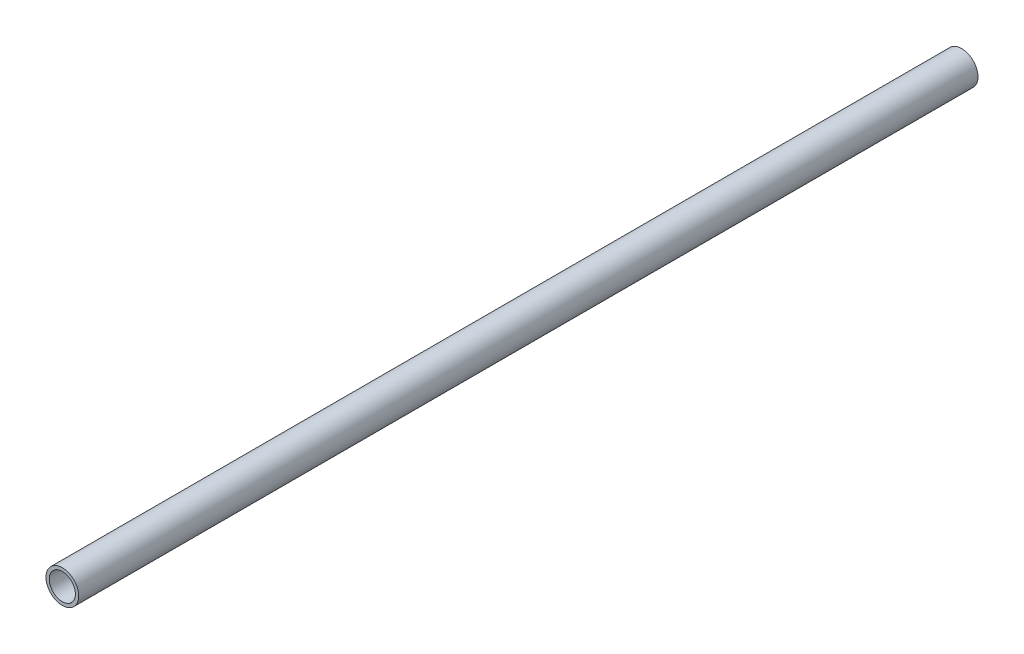
SolidWorks part; units mm, degrees
material "Thornel VCB-20 ｶｰﾎﾞﾝ ｸﾛｽ"
ref_plane "正面" through (0, 0, 0) normal (0, 0, 1) x (1, 0, 0)
ref_plane "平面" through (0, 0, 0) normal (0, 1, 0) x (1, 0, 0)
ref_plane "右側面" through (0, 0, 0) normal (1, 0, 0) x (0, 0, -1)
sketch "ｽｹｯﾁ1" plane through (0, 0, 0) normal (0, 0, 1) x (1, 0, 0)
  circle A0 centre (0, 0) radius 5
  circle A1 centre (0, 0) radius 4
  dimension "D1" = 10
  dimension "D2" = 8
extrude "ﾎﾞｽ - 押し出し1" add sketch "ｽｹｯﾁ1" along normal blind 275
sketch "ｽｹｯﾁ2" plane through (0, 0, 0) normal (0, 1, 0) x (1, 0, 0)
  line L0 (0, 0) -> (0, -275) construction
  line L1 (-4, -275) -> (4, -275) construction
